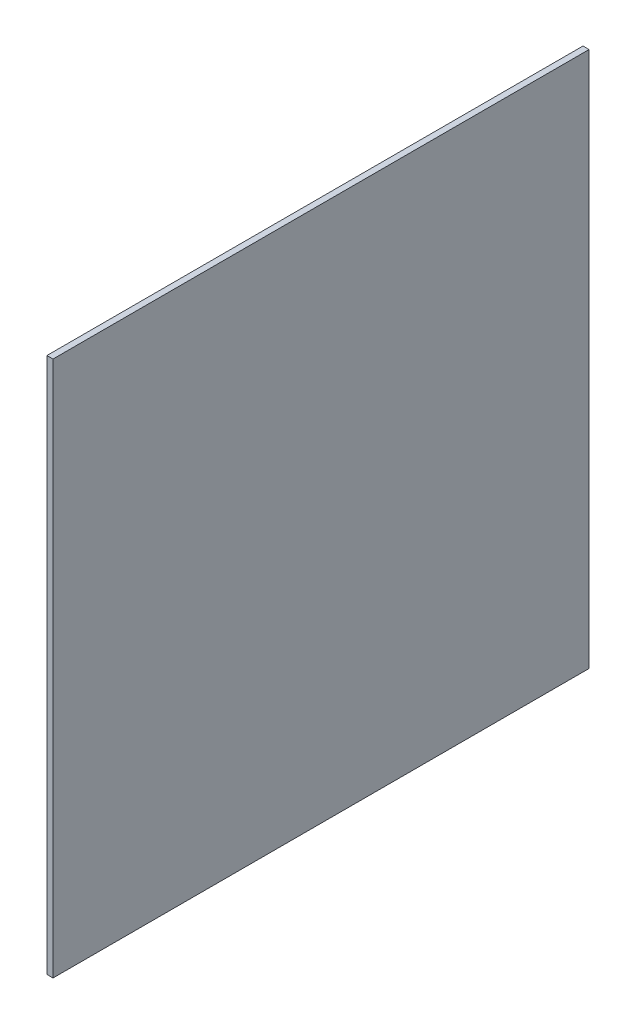
SolidWorks part; units mm, degrees
ref_plane "Front Plane" through (0, 0, 0) normal (0, 0, 1) x (1, 0, 0)
ref_plane "Top Plane" through (0, 0, 0) normal (0, 1, 0) x (1, 0, 0)
ref_plane "Right Plane" through (0, 0, 0) normal (1, 0, 0) x (0, 0, -1)
sketch "Sketch1" plane through (0, 0, 0) normal (1, 0, 0) x (0, 0, -1)
  line L1 (0, 0) -> (139.7, 0)
  line L2 (0, 0) -> (0, 139.7)
  line L3 (0, 139.7) -> (139.7, 139.7)
  line L4 (139.7, 0) -> (139.7, 139.7)
  dimension "D1" = 139.7
  dimension "D2" = 139.7
extrude "Boss-Extrude1" add sketch "Sketch1" along normal blind 1.5875
